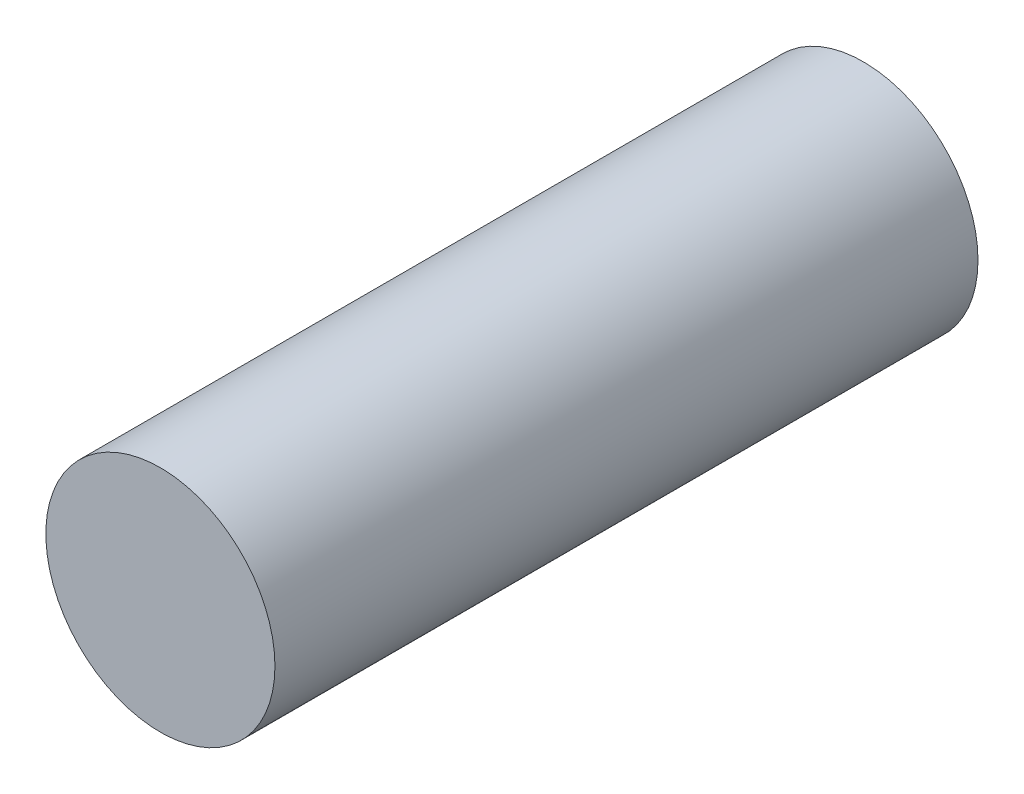
SolidWorks part; units mm, degrees
ref_plane "Front Plane" through (0, 0, 0) normal (0, 0, 1) x (1, 0, 0)
ref_plane "Top Plane" through (0, 0, 0) normal (0, 1, 0) x (1, 0, 0)
ref_plane "Right Plane" through (0, 0, 0) normal (1, 0, 0) x (0, 0, -1)
sketch "Sketch1" plane through (0, 0, 0) normal (0, 0, 1) x (1, 0, 0)
  circle A0 centre (0, 0) radius 14.85
  dimension "D1" = 29.7
extrude "Boss-Extrude1" add sketch "Sketch1" against normal blind 91.14
